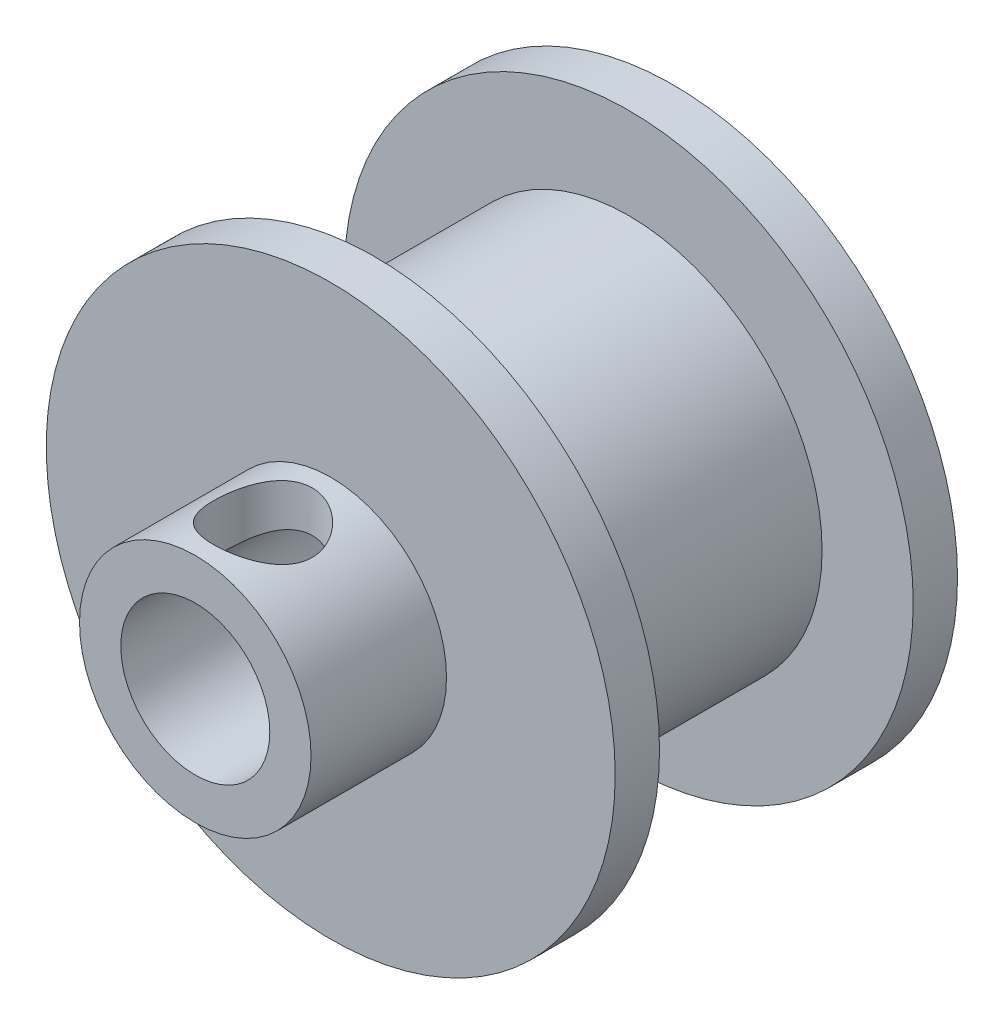
SolidWorks part; units mm, degrees
ref_plane "Plan de face" through (0, 0, 0) normal (0, 0, 1) x (1, 0, 0)
ref_plane "Plan de dessus" through (0, 0, 0) normal (0, 1, 0) x (1, 0, 0)
ref_plane "Plan de droite" through (0, 0, 0) normal (1, 0, 0) x (0, 0, -1)
sketch "Esquisse1" plane through (0, 0, 0) normal (0, 0, 1) x (1, 0, 0)
  circle A0 centre (0, 0) radius 3.025
  circle A1 centre (0, 0) radius 11.55
  dimension "D1" = 6.05
  dimension "D2" = 23.1
extrude "Boss.-Extru.1" add sketch "Esquisse1" along normal mid plane 13.9
sketch "Esquisse2" plane through (0, 0, 0) normal (0, 0, 1) x (1, 0, 0)
  circle A0 centre (0, 0) radius 7.85
  circle A1 centre (0, 0) radius 13.6604
  dimension "D1" = 15.7
extrude "Enlèv. mat.-Extru.1" cut sketch "Esquisse2" against normal mid plane 10.3
sketch "Esquisse4" plane through (0, 0, 6.95) normal (0, 0, 1) x (1, 0, 0)
  circle A0 centre (0, 0) radius 4.7
  circle A1 centre (0, 0) radius 3.025
  dimension "D1" = 9.4
extrude "Boss.-Extru.2" add sketch "Esquisse4" along normal blind 5.5
sketch "Esquisse5" plane through (0, 0, 0) normal (0, 1, 0) x (1, 0, 0)
  line L0 (-4.7, -12.45) -> (4.7, -12.45) construction
  circle A0 centre (0, -9.7) radius 2
  dimension "D1" = 4
  dimension "D2" = 2.75
extrude "Enlèv. mat.-Extru.3" cut sketch "Esquisse5" along normal through all
